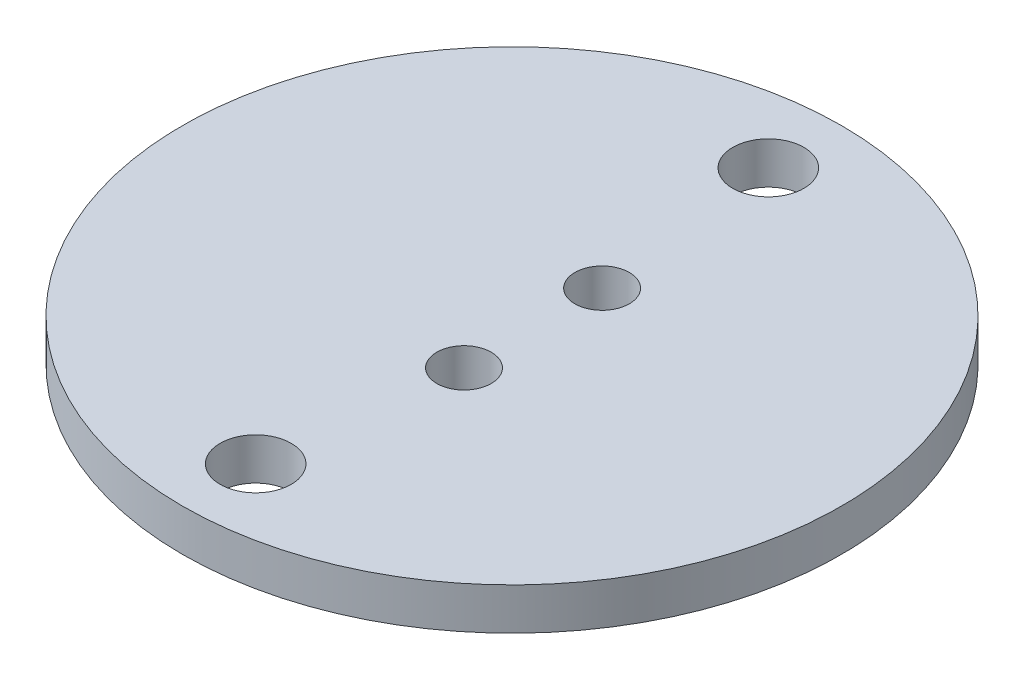
SolidWorks part; units mm, degrees
ref_plane "Front Plane" through (0, 0, 0) normal (0, 0, 1) x (1, 0, 0)
ref_plane "Top Plane" through (0, 0, 0) normal (0, 1, 0) x (1, 0, 0)
ref_plane "Right Plane" through (0, 0, 0) normal (1, 0, 0) x (0, 0, -1)
sketch "Sketch1" plane through (0, 0, 0) normal (0, 1, 0) x (1, 0, 0)
  circle A0 centre (0, 0) radius 7.875
  dimension "D1" = 15.75
extrude "Boss-Extrude1" add sketch "Sketch1" along normal blind 1
sketch "Sketch2" plane through (0, 1, 0) normal (0, 1, 0) x (1, 0, 0)
  line L0 (7.875, 0) -> (-7.875, 0) construction
  circle A0 centre (0, 6.125) radius 0.85
  circle A1 centre (0, 0) radius 7.875 construction
  circle A2 centre (0, -6.125) radius 0.85
  dimension "D1" = 1.7
  dimension "D2" = 0.9
  dimension "D3" = 10.55
extrude "Cut-Extrude1" cut sketch "Sketch2" against normal through all
sketch "Sketch3" plane through (0, 1, 0) normal (0, 1, 0) x (1, 0, 0)
  line L0 (0.5031, 1.65) -> (0.5031, -1.65) construction
  line L1 (0, 0) -> (2.2968, 7.5326) construction
  circle A0 centre (0.5031, 1.65) radius 0.65
  circle A1 centre (0, 0) radius 7.875 construction
  circle A2 centre (0.5031, -1.65) radius 0.65
  point P4 (1.2333, -1.0581)
  point P5 (0.5031, 0)
  point P6 (1.1641, -1.1338)
  point P10 (0.924, -1.3367)
  point P13 (1.25, -1.0384)
  dimension "D1" = 1.3
  dimension "D2" = 5.5
  dimension "D3" = 2
  dimension "D4" = 8.95
extrude "Cut-Extrude2" cut sketch "Sketch3" against normal blind 11
